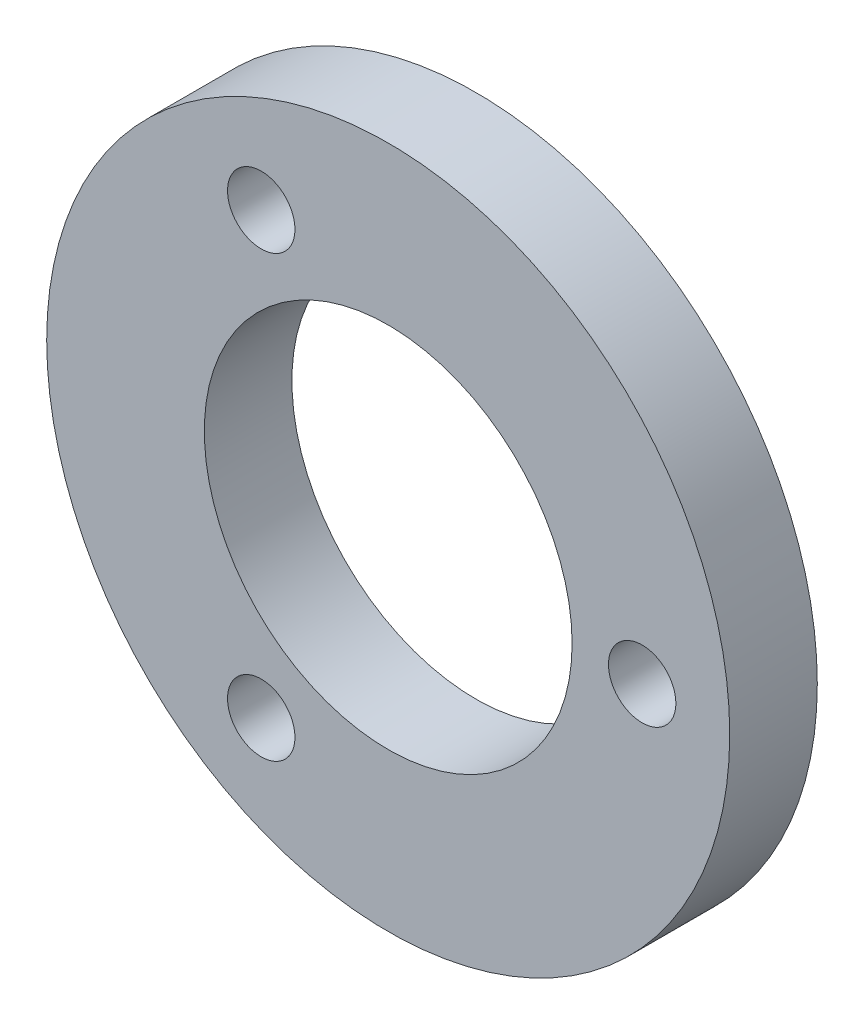
SolidWorks part; units mm, degrees
ref_plane "Plan de face" through (0, 0, 0) normal (0, 0, 1) x (1, 0, 0)
ref_plane "Plan de dessus" through (0, 0, 0) normal (0, 1, 0) x (1, 0, 0)
ref_plane "Plan de droite" through (0, 0, 0) normal (1, 0, 0) x (0, 0, -1)
sketch "Esquisse1" plane through (0, 0, 0) normal (0, 0, 1) x (1, 0, 0)
  circle A0 centre (0, 0) radius 10.5
  circle A1 centre (0, 0) radius 19.5
  circle A5 centre (-7.25, -12.5574) radius 1.925
  circle A6 centre (14.5, 0) radius 1.925
  circle A7 centre (-7.25, 12.5574) radius 1.925
  point P26 (0, 0)
  dimension "D1" = 21
  dimension "D2" = 3.85
  dimension "D5" = 39
  dimension "D3" = 14.5
  dimension "D4" = 3
extrude "Boss.-Extru.1" add sketch "Esquisse1" along normal blind 5
